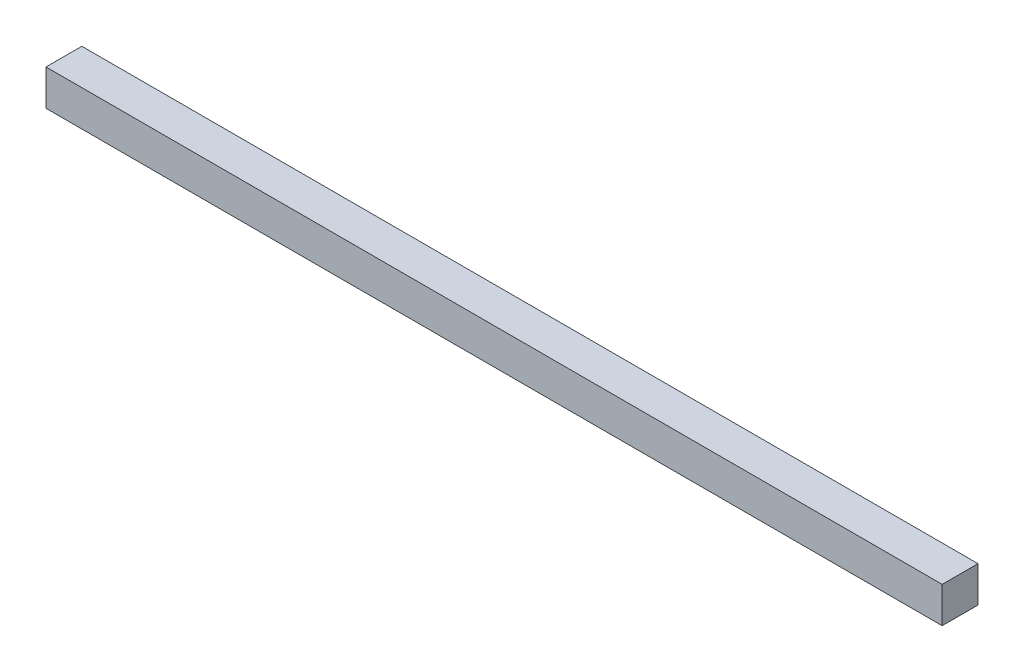
SolidWorks part; units mm, degrees
material "Pine"
ref_plane "Front Plane" through (0, 0, 0) normal (0, 0, 1) x (1, 0, 0)
ref_plane "Top Plane" through (0, 0, 0) normal (0, 1, 0) x (1, 0, 0)
ref_plane "Right Plane" through (0, 0, 0) normal (1, 0, 0) x (0, 0, -1)
sketch "Sketch1" plane through (0, 0, 0) normal (1, 0, 0) x (0, 0, -1)
  line L1 (-50, 50) -> (50, 50)
  line L2 (-50, 50) -> (-50, -50)
  line L3 (-50, -50) -> (50, -50)
  line L4 (50, 50) -> (50, -50)
  line L5 (-50, 50) -> (50, -50) construction
  line L6 (-50, -50) -> (50, 50) construction
  point P0 (0, 0)
  dimension "D1" = 100
  dimension "D2" = 100
extrude "Boss-Extrude1" add sketch "Sketch1" along normal mid plane 2500
